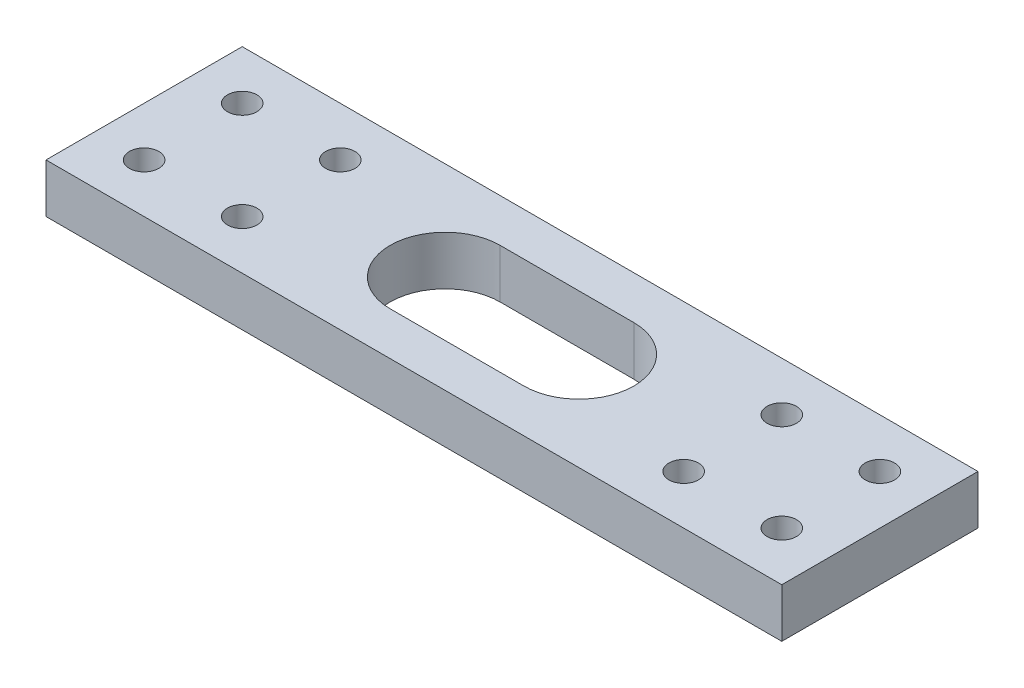
SolidWorks part; units mm, degrees
ref_plane "前视基准面" through (0, 0, 0) normal (0, 0, 1) x (1, 0, 0)
ref_plane "上视基准面" through (0, 0, 0) normal (0, 1, 0) x (1, 0, 0)
ref_plane "右视基准面" through (0, 0, 0) normal (1, 0, 0) x (0, 0, -1)
sketch "草图1" plane through (0, 0, 0) normal (0, 1, 0) x (1, 0, 0)
  line L1 (-37.5, -10) -> (37.5, -10)
  line L2 (-37.5, -10) -> (-37.5, 10)
  line L3 (-37.5, 10) -> (37.5, 10)
  line L4 (37.5, -10) -> (37.5, 10)
  line L5 (-37.5, -10) -> (37.5, 10) construction
  line L6 (-37.5, 10) -> (37.5, -10) construction
  point P0 (0, 0)
  dimension "D1" = 75
  dimension "D2" = 20
extrude "凸台-拉伸1" add sketch "草图1" along normal blind 5
sketch "草图2" plane through (0, 5, 0) normal (0, 1, 0) x (1, 0, 0)
  line L0 (37.5, -10) -> (37.5, 10) construction
  line L1 (37.5, 10) -> (-37.5, 10) construction
  circle A0 centre (22.5, 5) radius 1.5
  circle A1 centre (32.5, 5) radius 1.5
  circle A2 centre (22.5, -5) radius 1.5
  circle A3 centre (32.5, -5) radius 1.5
  dimension "D1" = 3
  dimension "D2" = 3
  dimension "D3" = 3
  dimension "D4" = 3
  dimension "D5" = 5
  dimension "D6" = 10
  dimension "D7" = 5
  dimension "D8" = 10
  dimension "D9" = 5
  dimension "D10" = 5
  dimension "D11" = 10
  dimension "D12" = 10
extrude "切除-拉伸1" cut sketch "草图2" against normal through all
sketch "草图3" plane through (0, 5, 0) normal (0, 1, 0) x (1, 0, 0)
  line L0 (6.8183, 0) -> (-6.8183, 0) construction
  line L1 (6.8183, -5.6023) -> (-6.8183, -5.6023)
  line L2 (6.8183, 5.6023) -> (-6.8183, 5.6023)
  line L3 (-37.5, 10) -> (-37.5, -10) construction
  arc A0 (6.8183, -5.6023) -> (6.8183, 5.6023) centre (6.8183, 0) ccw
  arc A1 (-6.8183, 5.6023) -> (-6.8183, -5.6023) centre (-6.8183, 0) ccw
  point P3 (0, 0)
  dimension "D1" = 37.5
extrude "切除-拉伸2" cut sketch "草图3" against normal through all
mirror "镜向1" about plane through (0, 0, 0) normal (1, 0, 0) of "切除-拉伸1"
